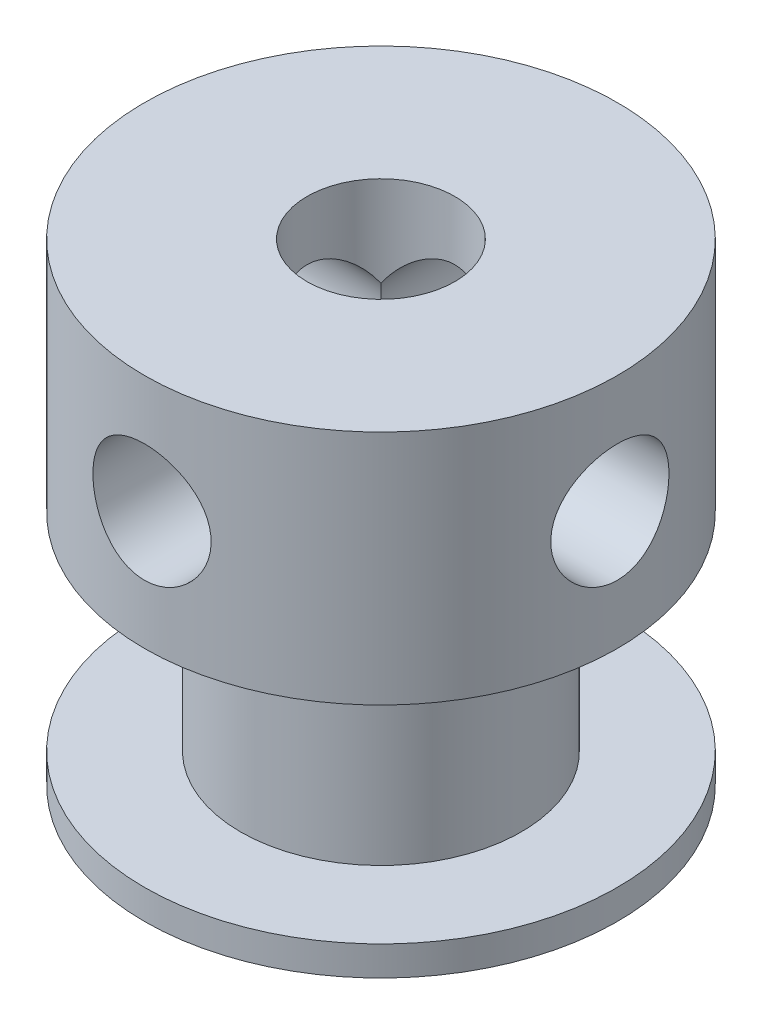
SolidWorks part; units mm, degrees
ref_plane "Front Plane" through (0, 0, 0) normal (0, 0, 1) x (1, 0, 0)
ref_plane "Top Plane" through (0, 0, 0) normal (0, 1, 0) x (1, 0, 0)
ref_plane "Right Plane" through (0, 0, 0) normal (1, 0, 0) x (0, 0, -1)
sketch "Sketch1" plane through (0, 0, 0) normal (0, 0, 1) x (1, 0, 0)
  line L0 (0, 17.6014) -> (0, -11.0259) construction
  line L1 (-2.5, 0) -> (-8, 0)
  line L2 (-8, 0) -> (-8, 1)
  line L3 (-8, 1) -> (-4.75, 1)
  line L4 (-4.75, 1) -> (-4.75, 8)
  line L5 (-4.75, 8) -> (-8, 8)
  line L6 (-8, 8) -> (-8, 16)
  line L9 (-8, 16) -> (-2.5, 16)
  line L10 (-2.5, 16) -> (-2.5, 0)
  point P5 (-12.7596, 16)
  point P11 (-12.102, 16)
  point P12 (-12.5717, 4.5)
  point P14 (-9.778, 4.5)
  dimension "D1" = 1
  dimension "D2" = 9.5
  dimension "D3" = 5
  dimension "D4" = 16
  dimension "D6" = 7
  dimension "D7" = 16
revolve "Revolve1" add sketch "Sketch1" angle 360 about L0
hole_wizard "Ø4.0 (4) Diameter Hole1" positions "Sketch3" profile "Sketch2" hole size "Ø4.0" standard "ISO"
sketch "Sketch3" plane through (0, 0, 0) normal (0, 0, 1) x (1, 0, 0)
  line L0 (-8, 16) -> (-8, 8) construction
  line L1 (-8, 12) -> (10.8494, 12)
  point P4 (0, 12)
  point P16 (0, 0)
sketch "Sketch2" plane through (0, 12, 0) normal (1, 0, 0) x (0, -1, 0)
  line L0 (0, 0) -> (0, 8)
  line L1 (0, 8) -> (2, 8)
  line L2 (2, 8) -> (2, 0)
  line L5 (2, 0) -> (0, 0)
  line L11 (0, -6.35) -> (0, 107.95) construction
  dimension "Thru Hole Dia." = 4
  dimension "Thru Hole Depth" = 8
pattern_circular "CirPattern1" count 4 every 90 of "Ø4.0 (4) Diameter Hole1"
